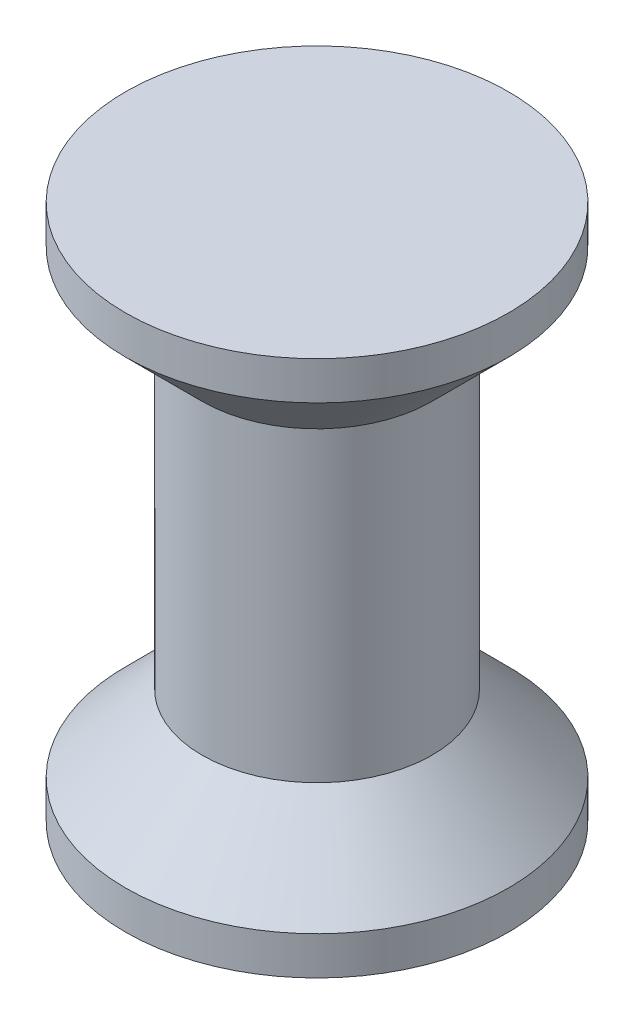
SolidWorks part; units mm, degrees
ref_plane "前视基准面" through (0, 0, 0) normal (0, 0, 1) x (1, 0, 0)
ref_plane "上视基准面" through (0, 0, 0) normal (0, 1, 0) x (1, 0, 0)
ref_plane "右视基准面" through (0, 0, 0) normal (1, 0, 0) x (0, 0, -1)
sketch "草图1" plane through (0, 0, 0) normal (0, 0, 1) x (1, 0, 0)
  line L0 (0, 35) -> (0, -79.6053) construction
  line L1 (0, 35) -> (25, 35)
  line L2 (25, 35) -> (25, 30)
  line L3 (25, 30) -> (15, 20)
  line L4 (15, 20) -> (15, -20)
  line L5 (-50.6968, 0) -> (68.3527, 0) construction
  line L6 (25, -30) -> (15, -20)
  line L7 (25, -35) -> (25, -30)
  line L8 (0, -35) -> (25, -35)
  line L9 (0, 35) -> (0, -35)
  point P11 (15, 0)
  dimension "D5" = 15
  dimension "D1" = 5
  dimension "D2" = 35
  dimension "D3" = 20
  dimension "D4" = 25
revolve "旋转1" add sketch "草图1" angle 360 about L9
